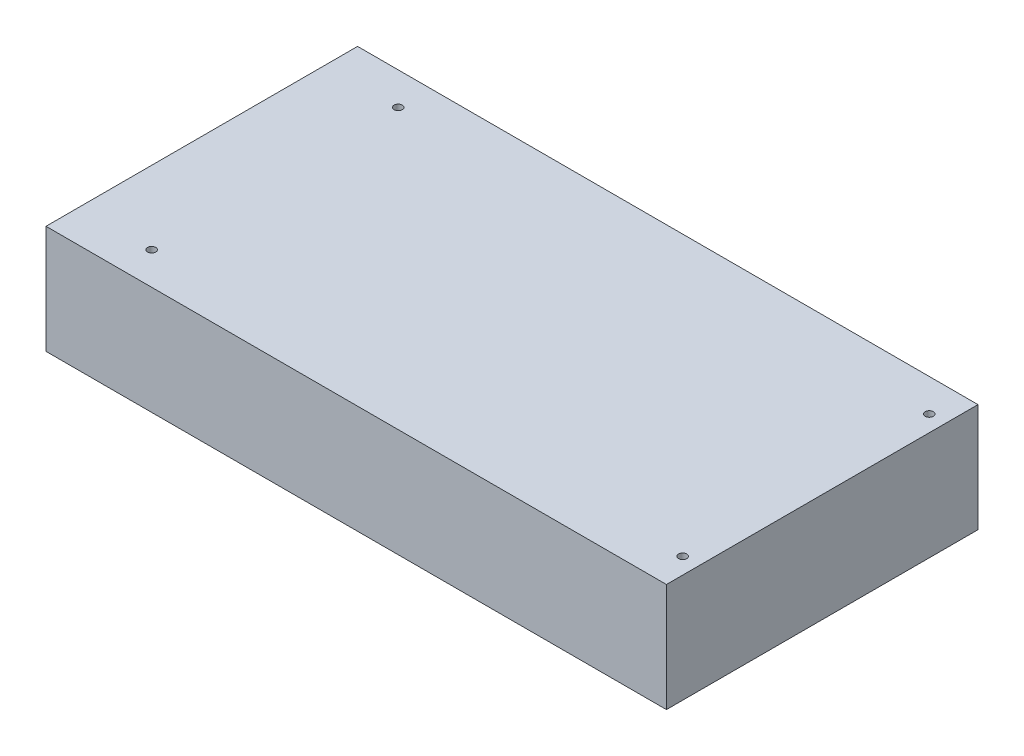
SolidWorks part; units mm, degrees
ref_plane "前视基准面" through (0, 0, 0) normal (0, 0, 1) x (1, 0, 0)
ref_plane "上视基准面" through (0, 0, 0) normal (0, 1, 0) x (1, 0, 0)
ref_plane "右视基准面" through (0, 0, 0) normal (1, 0, 0) x (0, 0, -1)
sketch "草图1" plane through (0, 0, 0) normal (0, 1, 0) x (1, 0, 0)
  line L1 (-1.2102, 35.3016) -> (227.7898, 35.3016)
  line L2 (-1.2102, 35.3016) -> (-1.2102, -79.6984)
  line L3 (-1.2102, -79.6984) -> (227.7898, -79.6984)
  line L4 (227.7898, 35.3016) -> (227.7898, -79.6984)
  line L7 (25.7898, 23.3016) -> (25.7898, -67.6984) construction
  line L8 (221.7898, 23.3016) -> (221.7898, -67.6984) construction
  line L243 (39.7898, 23.3016) -> (192.7898, -61.6984) construction
  line L244 (33.7898, 23.3016) -> (192.7898, 23.3016) construction
  line L245 (33.7898, 23.3016) -> (33.7898, -67.6984) construction
  line L246 (33.7898, -67.6984) -> (192.7898, -67.6984) construction
  line L247 (192.7898, 23.3016) -> (192.7898, -67.6984) construction
  line L248 (33.7898, 17.3016) -> (186.7898, -67.6984) construction
  line L249 (192.7898, 17.3016) -> (39.7898, -67.6984) construction
  line L250 (33.7898, -61.6984) -> (186.7898, 23.3016) construction
  circle A2 centre (25.7898, 23.3016) radius 1.5
  circle A3 centre (25.7898, -67.6984) radius 1.5
  circle A4 centre (221.7898, 23.3016) radius 1.5
  circle A5 centre (221.7898, -67.6984) radius 1.5
  arc A9 (114.7467, -16.7223) -> (111.8328, -16.7223) centre (113.2898, -14.0998) cw
  point P8 (-1.2102, -22.1984)
  point P9 (25.7898, -22.1984)
  point P14 (221.7898, -22.1984)
  point P15 (227.7898, -22.1984)
  point P16 (113.2898, 39.4338)
  point P19 (113.2898, 35.3016)
  point P27 (0, 0)
  point P33 (0, 0)
  point P47 (113.2898, -26.865)
  point P50 (121.6898, -22.1984)
  point P53 (113.2898, -17.5317)
  point P56 (104.8898, -22.1984)
  dimension "D4" = 27
  dimension "D3" = 91
  dimension "D6" = 91
  dimension "D8" = 6
  dimension "D9" = 6
  dimension "D1" = 229
  dimension "D2" = 35
  dimension "D5" = 6
  dimension "D7" = 35
  dimension "D10" = 6
  dimension "D11" = 6
  dimension "D12" = 115
  dimension "D13" = 6
  dimension "D14" = 6
  dimension "D15" = 6
  dimension "D16" = 6
extrude "凸台-拉伸1" add sketch "草图1" along normal blind 40
